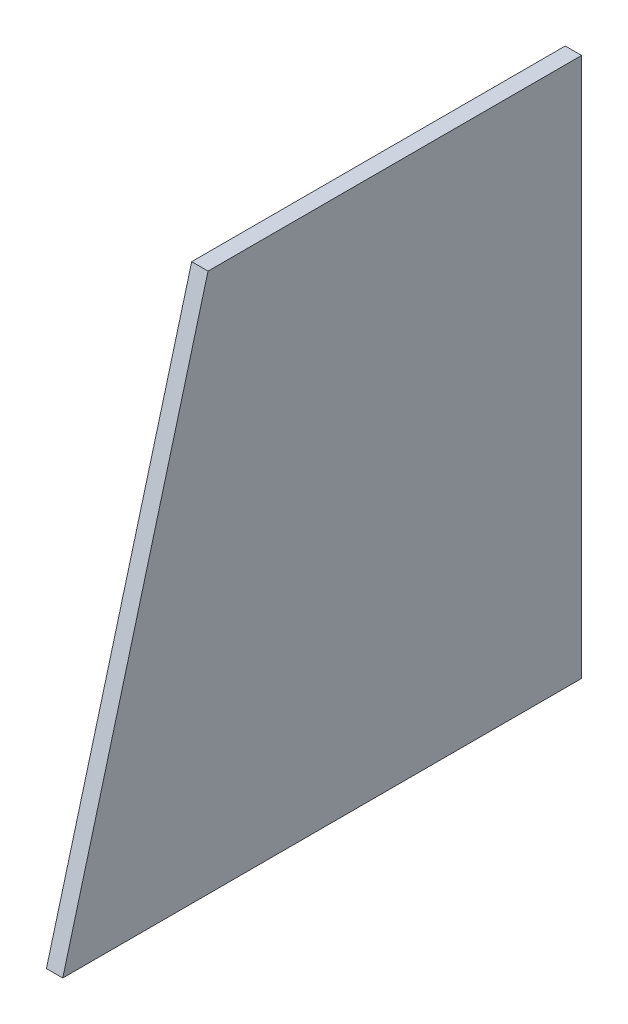
SolidWorks part; units mm, degrees
ref_plane "Front Plane" through (0, 0, 0) normal (0, 0, 1) x (1, 0, 0)
ref_plane "Top Plane" through (0, 0, 0) normal (0, 1, 0) x (1, 0, 0)
ref_plane "Right Plane" through (0, 0, 0) normal (1, 0, 0) x (0, 0, -1)
sketch "Sketch1" plane through (0, 0, 0) normal (1, 0, 0) x (0, 0, -1)
  line L0 (0, 0) -> (44.45, 165.1)
  line L1 (44.45, 165.1) -> (158.75, 165.1)
  line L2 (158.75, 165.1) -> (158.75, 0)
  line L3 (158.75, 0) -> (0, 0)
  line L4 (0, 0) -> (0, 165.1) construction
  dimension "D1" = 158.75
  dimension "D2" = 165.1
  dimension "D3" = 114.3
extrude "Boss-Extrude1" add sketch "Sketch1" along normal blind 5 contours L0 L1 L2 L3
